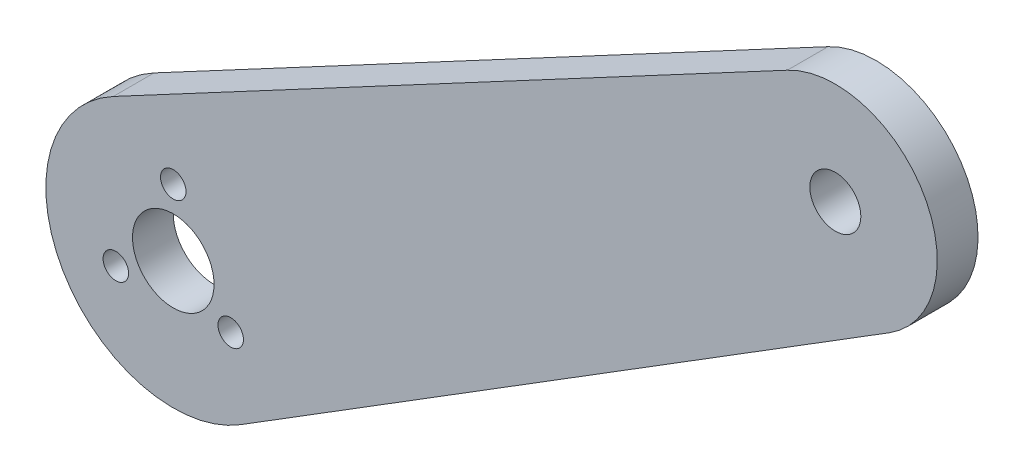
SolidWorks part; units mm, degrees
material "Thornel Mat VMA"
ref_plane "Front Plane" through (0, 0, 0) normal (0, 0, 1) x (1, 0, 0)
ref_plane "Top Plane" through (0, 0, 0) normal (0, 1, 0) x (1, 0, 0)
ref_plane "Right Plane" through (0, 0, 0) normal (1, 0, 0) x (0, 0, -1)
sketch "Sketch1" plane through (0, 0, 0) normal (0, 0, 1) x (1, 0, 0)
  line L0 (0, 0) -> (64.9519, 37.5) construction
  line L1 (0, 0) -> (51.301, 0) construction
  line L2 (60.2434, 46.3221) -> (-5.8857, 11.0276)
  line L3 (6.6074, -10.611) -> (70.2378, 29.0112)
  line L4 (5.6338, -3.2527) -> (-5.6338, -3.2527) construction
  line L5 (-5.6338, -3.2527) -> (0, 6.5054) construction
  line L6 (0, 6.5054) -> (5.6338, -3.2527) construction
  circle A5 centre (0, 0) radius 4
  circle A6 centre (0, 6.5054) radius 1.25
  circle A7 centre (5.6338, -3.2527) radius 1.25
  circle A8 centre (-5.6338, -3.2527) radius 1.25
  circle A9 centre (0, 0) radius 12.5
  circle A10 centre (64.9519, 37.5) radius 2.5
  circle A11 centre (64.9519, 37.5) radius 10
  circle A12 centre (0, 0) radius 6.5054 construction
  point P1 (0, 0)
  point P3 (-3.9454, 5.1725)
  point P5 (-4.8758, -4.3066)
  dimension "D2" = 5
  dimension "D4" = 20
  dimension "D5" = 25
  dimension "D7" = 8
  dimension "D8" = 2.5
  dimension "D1" = 75
  dimension "D3" = 30
  dimension "D6" = 11.2677
extrude "Boss-Extrude1" add sketch "Sketch1" along normal blind 4 contours A9 A5 A6 A7 A8 | A11 L2 A9 L3 | A11 A10
